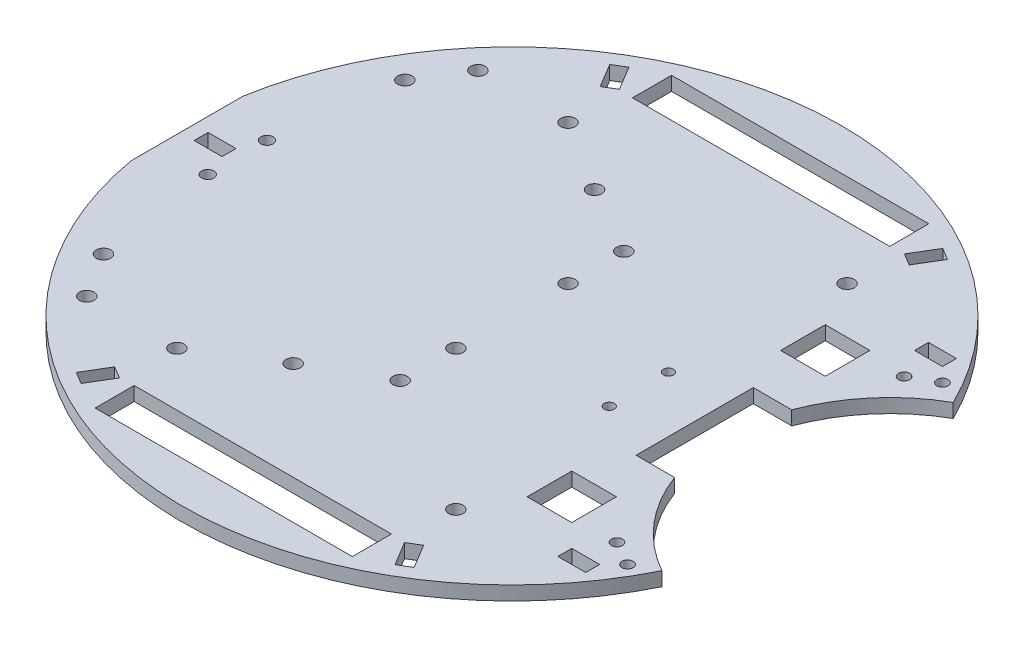
SolidWorks part; units mm, degrees
material "Acrylic (Medium-high impact)"
ref_plane "Front Plane" through (0, 0, 0) normal (0, 0, 1) x (1, 0, 0)
ref_plane "Top Plane" through (0, 0, 0) normal (0, 1, 0) x (1, 0, 0)
ref_plane "Right Plane" through (0, 0, 0) normal (1, 0, 0) x (0, 0, -1)
sketch "Sketch1" plane through (0, 0, 0) normal (0, 1, 0) x (1, 0, 0)
  line L0 (67.2709, 33.1606) -> (86.0323, 0) construction
  line L1 (86.0323, 0) -> (67.2709, -33.1606) construction
  line L2 (0, 65.5895) -> (0, 75) construction
  line L3 (-29.2721, -56.6995) -> (29.2721, -56.6995)
  line L4 (-29.2721, -56.6995) -> (-29.2721, -65.5895)
  line L5 (-29.2721, -65.5895) -> (29.2721, -65.5895)
  line L6 (29.2721, -56.6995) -> (29.2721, -65.5895)
  line L7 (-29.2721, 65.5895) -> (29.2721, 65.5895)
  line L8 (-29.2721, 65.5895) -> (-29.2721, 56.6995)
  line L9 (-29.2721, 56.6995) -> (29.2721, 56.6995)
  line L10 (29.2721, 65.5895) -> (29.2721, 56.6995)
  line L11 (29.2721, 65.5895) -> (30.566, 68.4888) construction
  line L12 (29.2721, -65.5895) -> (30.566, -68.4888) construction
  line L13 (-62.4869, 6.731) -> (-62.4869, -6.731) construction
  line L14 (-62.4869, 0) -> (-73.9169, 0) construction
  line L15 (67.2709, -33.1606) -> (50.3358, -63.0933) construction
  line L16 (58.9661, -42.1806) -> (52.6161, -42.1806)
  line L17 (58.9661, -42.1806) -> (58.9661, -39.0056)
  line L18 (58.9661, -39.0056) -> (52.6161, -39.0056)
  line L19 (52.6161, -42.1806) -> (52.6161, -39.0056)
  line L20 (58.9661, 42.1806) -> (52.6161, 42.1806)
  line L21 (58.9661, 42.1806) -> (58.9661, 39.0056)
  line L22 (47.5361, 23.7656) -> (47.5361, 33.9256)
  line L23 (0, 0) -> (86.0323, 0) construction
  line L24 (52.6161, 42.1806) -> (52.6161, 39.0056)
  line L25 (58.9661, 39.0056) -> (52.6161, 39.0056)
  line L26 (56.5708, -32.6791) -> (62.1411, -35.8306) construction
  line L27 (50.3421, 13.335) -> (41.5823, 13.335)
  line L28 (-31.75, -44.5075) -> (0, -12.7575) construction
  line L29 (0, -12.7575) -> (31.75, -44.5075) construction
  line L30 (-31.75, -44.5075) -> (31.75, -44.5075) construction
  line L31 (0, -12.7575) -> (0, -44.5075) construction
  line L32 (41.5823, 13.335) -> (41.5823, -13.335)
  line L33 (41.5823, -13.335) -> (50.3421, -13.335)
  line L34 (37.3761, -23.7656) -> (47.5361, -23.7656)
  line L35 (50.3421, -13.335) -> (50.3421, 0) construction
  line L36 (50.3421, 0) -> (50.3421, 13.335) construction
  line L37 (32.441, -56.8953) -> (35.7191, -62.3337)
  line L38 (32.441, -56.8953) -> (35.1602, -55.2563)
  line L39 (35.7191, -62.3337) -> (38.4383, -60.6947)
  line L40 (35.1602, -55.2563) -> (38.4383, -60.6947)
  line L41 (-58.6769, -34.29) -> (-58.6769, 34.29) construction
  line L42 (37.3761, -23.7656) -> (37.3761, -33.9256)
  line L43 (-58.6769, 0) -> (-62.4869, 0) construction
  line L44 (37.3761, -33.9256) -> (47.5361, -33.9256)
  line L45 (47.5361, -23.7656) -> (47.5361, -33.9256)
  line L46 (37.3761, 33.9256) -> (47.5361, 33.9256)
  line L47 (-73.9169, 12.7) -> (-73.9169, -12.7)
  line L48 (37.3761, 23.7656) -> (37.3761, 33.9256)
  line L49 (37.3761, 23.7656) -> (47.5361, 23.7656)
  line L50 (-58.6769, 34.29) -> (-15.4969, 34.29) construction
  line L51 (-15.4969, 34.29) -> (-15.4969, -34.29) construction
  line L52 (-15.4969, -34.29) -> (-58.6769, -34.29) construction
  line L53 (-52.2677, -44.5075) -> (-57.1023, -48.6243) construction
  line L54 (28.8823, 6.731) -> (28.8823, 0) construction
  line L55 (0, 0) -> (28.8823, 0) construction
  line L56 (28.8823, 0) -> (28.8823, -6.731) construction
  line L58 (32.441, -56.8953) -> (38.4383, -60.6947) construction
  line L59 (35.7191, -62.3337) -> (35.1602, -55.2563) construction
  line L63 (33.8006, -56.0758) -> (0, 0) construction
  line L64 (37.0787, -61.5142) -> (38.7178, -64.2334) construction
  line L65 (-32.441, -56.8953) -> (-35.1602, -55.2563)
  line L66 (-32.441, -56.8953) -> (-35.7191, -62.3337)
  line L67 (-35.7191, -62.3337) -> (-38.4383, -60.6947)
  line L68 (-35.1602, -55.2563) -> (-38.4383, -60.6947)
  line L69 (-35.1602, 55.2563) -> (-38.4383, 60.6947)
  line L70 (-32.441, 56.8953) -> (-35.1602, 55.2563)
  line L71 (-32.441, 56.8953) -> (-35.7191, 62.3337)
  line L72 (-35.7191, 62.3337) -> (-38.4383, 60.6947)
  line L73 (35.1602, 55.2563) -> (38.4383, 60.6947)
  line L74 (32.441, 56.8953) -> (35.1602, 55.2563)
  line L75 (32.441, 56.8953) -> (35.7191, 62.3337)
  line L76 (35.7191, 62.3337) -> (38.4383, 60.6947)
  line L77 (-73.9169, 0) -> (-70.7419, 0) construction
  line L78 (-70.7419, 1.5875) -> (-64.3919, 1.5875)
  line L79 (-70.7419, 1.5875) -> (-70.7419, -1.5875)
  line L80 (-70.7419, -1.5875) -> (-64.3919, -1.5875)
  line L81 (-64.3919, 1.5875) -> (-64.3919, -1.5875)
  arc A0 (67.2709, 33.1606) -> (-73.9169, 12.7) centre (0, 0) ccw
  arc A1 (67.2709, -33.1606) -> (55.0862, -22.225) centre (86.0323, 0) cw
  circle A2 centre (-62.4869, 6.731) radius 1.397
  circle A3 centre (-62.4869, -6.731) radius 1.397
  circle A4 centre (-31.75, -44.5075) radius 1.651
  circle A5 centre (31.75, -44.5075) radius 1.651
  circle A6 centre (31.75, 44.5075) radius 1.651
  circle A7 centre (0, -12.7575) radius 1.651
  circle A8 centre (-31.75, 44.5075) radius 1.651
  circle A9 centre (0, 12.7575) radius 1.651
  circle A10 centre (28.8823, 6.731) radius 1.143
  arc A11 (55.0862, -22.225) -> (50.3421, -13.335) centre (86.0323, 0) cw
  circle A12 centre (-58.6769, 34.29) radius 1.651
  circle A13 centre (62.1411, -35.8306) radius 1.27
  circle A14 centre (56.5708, -32.6791) radius 1.27
  circle A15 centre (-58.6769, -34.29) radius 1.651
  arc A16 (50.3421, 13.335) -> (67.2709, 33.1606) centre (86.0323, 0) cw
  arc A17 (-73.9169, -12.7) -> (67.2709, -33.1606) centre (0, 0) ccw
  circle A18 centre (28.8823, -6.731) radius 1.143
  circle A21 centre (0, -44.5075) radius 1.6319 construction
  circle A23 centre (0, -12.7575) radius 1.6319 construction
  circle A24 centre (0, -25.4575) radius 1.651
  circle A25 centre (56.5708, 32.6791) radius 1.27
  circle A26 centre (62.1411, 35.8306) radius 1.27
  circle A27 centre (0, 25.4575) radius 1.651
  circle A28 centre (-15.4969, 34.29) radius 1.651
  circle A29 centre (-15.4969, -34.29) radius 1.651
  circle A30 centre (-52.2677, -44.5075) radius 1.651
  circle A31 centre (-52.2677, 44.5075) radius 1.651
  point P50 (41.5823, 0)
  point P56 (47.9323, 0)
  point P63 (35.4397, -58.795)
  dimension "D1" = 150
  dimension "D7" = 11.43
  dimension "D8" = 2.794
  dimension "D14" = 63.5
  dimension "D16" = 3.302
  dimension "D22" = 5.08
  dimension "D27" = 3.302
  dimension "D36" = 2.6701
  dimension "D41" = 2.54
  dimension "D31" = 2.286
  dimension "D2" = 121
  dimension "D3" = 38.1
  dimension "D4" = 58.5441
  dimension "D5" = 8.89
  dimension "D6" = 3.175
  dimension "D9" = 13.462
  dimension "D10" = 6.35
  dimension "D11" = 3.175
  dimension "D12" = 3.175
  dimension "D13" = 3.175
  dimension "D15" = 6.35
  dimension "D17" = 5.1299
  dimension "D18" = 25.4
  dimension "D19" = 26.67
  dimension "D20" = 10.16
  dimension "D21" = 10.16
  dimension "D23" = 38.1
  dimension "D24" = 5.08
  dimension "D25" = 15.24
  dimension "D26" = 68.58
  dimension "D28" = 44.45
  dimension "D29" = 43.18
  dimension "D30" = 6.35
  dimension "D32" = 13.462
  dimension "D33" = 12.7
  dimension "D37" = 3.175
  dimension "D38" = 3.175
  dimension "D39" = 3.175
  dimension "D40" = 6.4
extrude "Boss-Extrude1" add sketch "Sketch1" along normal blind 3.175
equation "\"Diameter\"= 2.75"
equation "\"D4@Sketch1\"=\"Diameter\"*sin(arccos(1-(5/(4*\"Diameter\"))))"
